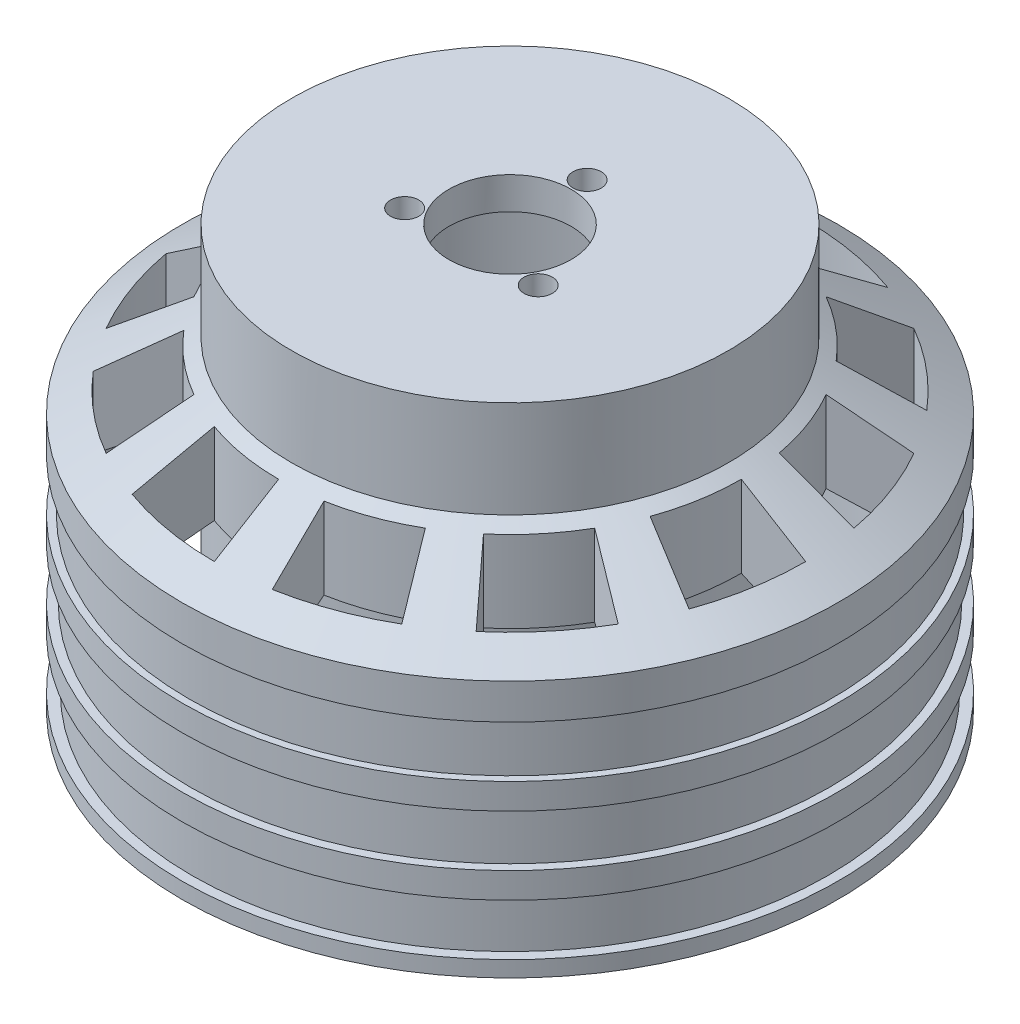
SolidWorks part; units mm, degrees
ref_plane "前视基准面" through (0, 0, 0) normal (0, 0, 1) x (1, 0, 0)
ref_plane "上视基准面" through (0, 0, 0) normal (0, 1, 0) x (1, 0, 0)
ref_plane "右视基准面" through (0, 0, 0) normal (1, 0, 0) x (0, 0, -1)
other "Configuration Table"
sketch "草图1" plane through (0, 0, 0) normal (0, 0, 1) x (1, 0, 0)
  line L0 (0, 0) -> (0, 45.6228) construction
  line L1 (0, 2.5) -> (17, 2.5)
  line L2 (0, 2.5) -> (0, 0)
  line L3 (0, 0) -> (14, 0)
  line L6 (17, 2.5) -> (17, -24)
  line L7 (17, -24) -> (14, -24)
  line L8 (14, 0) -> (14, -24)
  dimension "D1" = 14
  dimension "D2" = 2.5
  dimension "D3" = 3
  dimension "D4" = 24
revolve "旋转1" add sketch "草图1" angle 360 about L0
sketch "草图2" plane through (0, 2.5, 0) normal (0, 1, 0) x (1, 0, 0)
  circle A1 centre (0, 0) radius 6 construction
  circle A2 centre (0, 0) radius 4.75
  circle A5 centre (0, 6) radius 1.1
  circle A6 centre (5.1962, -3) radius 1.1
  circle A7 centre (-5.1962, -3) radius 1.1
  point P12 (0, 0)
  point P22 (6.5066, 3.7302)
  point P37 (0, 0)
  point P39 (16.1363, 11.1011)
  point P45 (0, 0)
  dimension "D1" = 2.2
  dimension "D2" = 12
  dimension "D3" = 9.5
  dimension "D4" = 3
extrude "切除-拉伸1" cut sketch "草图2" against normal blind 10
sketch "草图6" plane through (0, 0, 0) normal (1, 0, 0) x (0, 0, -1)
  line L0 (17, -11.5457) -> (17, -5.0565)
  line L2 (25.5, -10.238) -> (25.5, -30.238)
  line L4 (17, -8.3011) -> (22.5947, -8.3011) construction
  line L5 (0, 0) -> (0, -13) construction
  line L6 (25.5, -10.238) -> (17, -5.0565)
  line L7 (25.5, -30.238) -> (22.5947, -28.3539)
  line L8 (17, -24) -> (17, 2.5) construction
  line L9 (17, -24) -> (17, 2.5) construction
  line L10 (17, -11.5457) -> (22.5947, -14.088)
  line L11 (22.5947, -14.088) -> (22.5947, -28.3539)
  point P2 (22.5947, -16.5161)
  point P14 (15.8, -3.1759)
  point P15 (15.8, -11.917)
  point P16 (22.3894, -15.6877)
  point P17 (15.8, -11.5457)
  point P18 (22.5947, -14.088)
  dimension "D1" = 25.5
  dimension "D2" = 20
revolve "旋转3" add sketch "草图6" angle 360 about L5
sketch "草图7" plane through (0, 0, 0) normal (0, 1, 0) x (1, 0, 0)
  line L0 (0, 23) -> (0, 18)
  line L1 (7.7325, 21.6612) -> (6.0515, 16.9523)
  line L2 (17.5272, 14.8929) -> (13.7169, 11.6553)
  line L3 (11.5, 19.9186) -> (9, 15.5885)
  line L4 (22.6254, 4.1341) -> (17.7068, 3.2353)
  line L5 (19.9186, 11.5) -> (15.5885, 9)
  line L6 (21.6612, -7.7325) -> (16.9523, -6.0515)
  line L7 (23, 0) -> (18, 0)
  line L8 (14.8929, -17.5272) -> (11.6553, -13.7169)
  line L9 (19.9186, -11.5) -> (15.5885, -9)
  line L10 (4.1341, -22.6254) -> (3.2353, -17.7068)
  line L11 (11.5, -19.9186) -> (9, -15.5885)
  line L12 (-7.7325, -21.6612) -> (-6.0515, -16.9523)
  line L13 (0, -23) -> (0, -18)
  line L14 (-17.5272, -14.8929) -> (-13.7169, -11.6553)
  line L15 (-11.5, -19.9186) -> (-9, -15.5885)
  line L16 (-22.6254, -4.1341) -> (-17.7068, -3.2353)
  line L17 (-19.9186, -11.5) -> (-15.5885, -9)
  line L18 (-21.6612, 7.7325) -> (-16.9523, 6.0515)
  line L19 (-23, 0) -> (-18, 0)
  line L20 (-14.8929, 17.5272) -> (-11.6553, 13.7169)
  line L21 (-19.9186, 11.5) -> (-15.5885, 9)
  line L22 (-4.1341, 22.6254) -> (-3.2353, 17.7068)
  line L23 (-11.5, 19.9186) -> (-9, 15.5885)
  arc A0 (-11.6553, 13.7169) -> (-15.5885, 9) centre (0, 0) ccw
  arc A1 (-14.8929, 17.5272) -> (-19.9186, 11.5) centre (0, 0) ccw
  arc A2 (-21.6612, 7.7325) -> (-23, 0) centre (0, 0) ccw
  arc A3 (-16.9523, 6.0515) -> (-18, 0) centre (0, 0) ccw
  arc A4 (-17.7068, -3.2353) -> (-15.5885, -9) centre (0, 0) ccw
  arc A5 (-22.6254, -4.1341) -> (-19.9186, -11.5) centre (0, 0) ccw
  arc A6 (-17.5272, -14.8929) -> (-11.5, -19.9186) centre (0, 0) ccw
  arc A7 (-13.7169, -11.6553) -> (-9, -15.5885) centre (0, 0) ccw
  arc A8 (-6.0515, -16.9523) -> (0, -18) centre (0, 0) ccw
  arc A9 (-7.7325, -21.6612) -> (0, -23) centre (0, 0) ccw
  arc A10 (4.1341, -22.6254) -> (11.5, -19.9186) centre (0, 0) ccw
  arc A11 (3.2353, -17.7068) -> (9, -15.5885) centre (0, 0) ccw
  arc A12 (11.6553, -13.7169) -> (15.5885, -9) centre (0, 0) ccw
  arc A13 (14.8929, -17.5272) -> (19.9186, -11.5) centre (0, 0) ccw
  arc A14 (21.6612, -7.7325) -> (23, 0) centre (0, 0) ccw
  arc A15 (16.9523, -6.0515) -> (18, 0) centre (0, 0) ccw
  arc A16 (17.7068, 3.2353) -> (15.5885, 9) centre (0, 0) ccw
  arc A17 (22.6254, 4.1341) -> (19.9186, 11.5) centre (0, 0) ccw
  arc A18 (17.5272, 14.8929) -> (11.5, 19.9186) centre (0, 0) ccw
  arc A19 (13.7169, 11.6553) -> (9, 15.5885) centre (0, 0) ccw
  arc A20 (6.0515, 16.9523) -> (0, 18) centre (0, 0) ccw
  arc A21 (7.7325, 21.6612) -> (0, 23) centre (0, 0) ccw
  arc A22 (-4.1341, 22.6254) -> (-11.5, 19.9186) centre (0, 0) ccw
  arc A23 (-3.2353, 17.7068) -> (-9, 15.5885) centre (0, 0) ccw
  point P55 (0, 0)
  dimension "D1" = 36
  dimension "D2" = 46
  dimension "D3" = 12
extrude "切除-拉伸2" cut sketch "草图7" against normal mid plane 35
ref_plane "基准面2" through (0, -13, 0) normal (0, 1, 0) x (1, 0, 0)
sketch "草图9" plane through (0, -13, 0) normal (0, 1, 0) x (1, 0, 0)
  circle A0 centre (0, 0) radius 24.9543
  circle A1 centre (0, 0) radius 26
extrude "切除-拉伸4" cut sketch "草图9" against normal blind 4
ref_plane "基准面3" through (0, -19, 0) normal (0, 1, 0) x (1, 0, 0)
sketch "草图10" plane through (0, -19, 0) normal (0, 1, 0) x (1, 0, 0)
  circle A0 centre (0, 0) radius 24.8511
  circle A1 centre (0, 0) radius 27.1557
extrude "切除-拉伸5" cut sketch "草图10" against normal blind 4
ref_plane "基准面4" through (0, -25, 0) normal (0, 1, 0) x (1, 0, 0)
sketch "草图11" plane through (0, -25, 0) normal (0, 1, 0) x (1, 0, 0)
  circle A0 centre (0, 0) radius 24.7362
  circle A1 centre (0, 0) radius 26.971
extrude "切除-拉伸6" cut sketch "草图11" against normal blind 4
